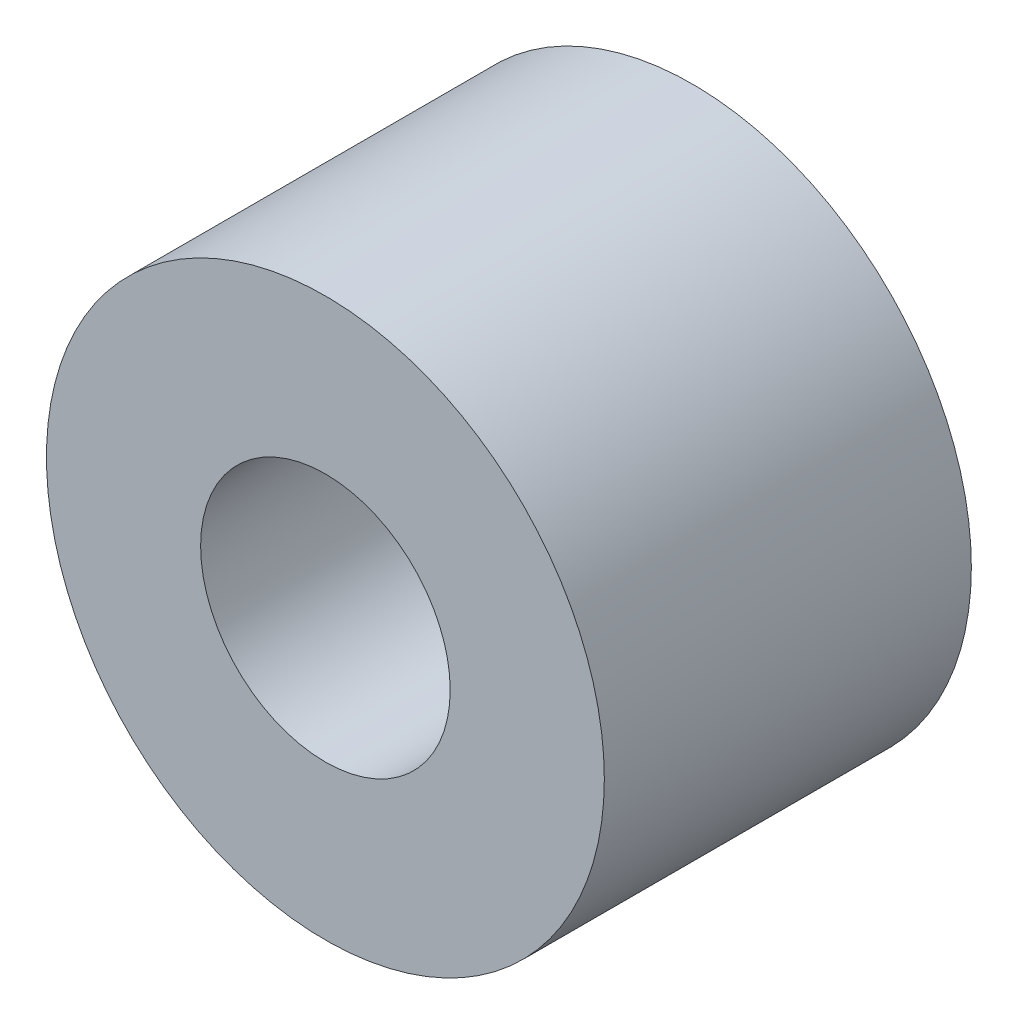
SolidWorks part; units mm, degrees
material "AISI 1020"
ref_plane "Plano frontal" through (0, 0, 0) normal (0, 0, 1) x (1, 0, 0)
ref_plane "Plano superior" through (0, 0, 0) normal (0, 1, 0) x (1, 0, 0)
ref_plane "Plano direito" through (0, 0, 0) normal (1, 0, 0) x (0, 0, -1)
sketch "Esboço1" plane through (0, 0, 0) normal (0, 0, 1) x (1, 0, 0)
  circle A0 centre (0, 0) radius 19
  circle A1 centre (0, 0) radius 8.5
  dimension "D1" = 38
  dimension "D2" = 17
extrude "Extrusão1" add sketch "Esboço1" along normal blind 25
